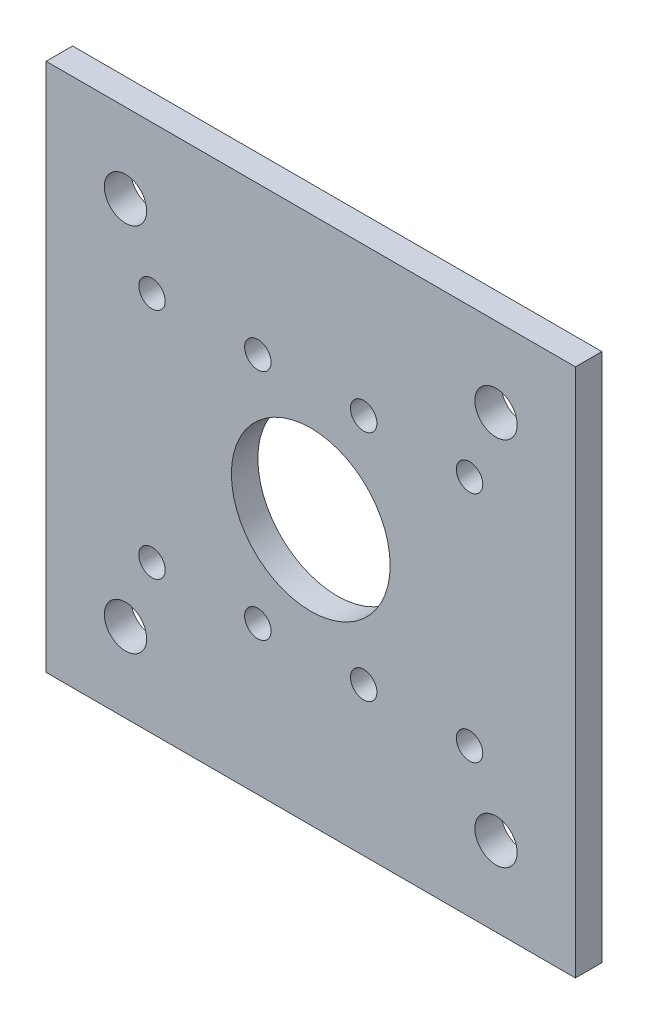
SolidWorks part; units mm, degrees
material "6063-T1"
ref_plane "Front Plane" through (0, 0, 0) normal (0, 0, 1) x (1, 0, 0)
ref_plane "Top Plane" through (0, 0, 0) normal (0, 1, 0) x (1, 0, 0)
ref_plane "Right Plane" through (0, 0, 0) normal (1, 0, 0) x (0, 0, -1)
sketch "Sketch1" plane through (0, 0, 0) normal (0, 0, 1) x (1, 0, 0)
  line L1 (0, 0) -> (100, 0)
  line L2 (0, 0) -> (0, 100)
  line L3 (0, 100) -> (100, 100)
  line L4 (100, 0) -> (100, 100)
  circle A1 centre (15, 85) radius 4
  circle A2 centre (85, 85) radius 4
  circle A3 centre (85, 15) radius 4
  circle A4 centre (15, 15) radius 4
  circle A5 centre (50, 50) radius 15
  dimension "D3" = 30
  dimension "D4" = 50
  dimension "D5" = 50
  dimension "D6" = 8
  dimension "D7" = 8
  dimension "D8" = 8
  dimension "D9" = 8
  dimension "D10" = 15
  dimension "D11" = 15
  dimension "D12" = 15
  dimension "D13" = 15
  dimension "D14" = 15
  dimension "D15" = 15
  dimension "D16" = 15
  dimension "D17" = 15
  dimension "D1" = 100
  dimension "D2" = 100
extrude "Boss-Extrude1" add sketch "Sketch1" along normal blind 5
sketch "Sketch2" plane through (0, 0, 5) normal (0, 0, 1) x (1, 0, 0)
  line L0 (0, 100) -> (0, 0) construction
  line L1 (100, 0) -> (100, 100) construction
  line L2 (100, 100) -> (0, 100) construction
  line L3 (0, 0) -> (100, 0) construction
  circle A1 centre (20, 72) radius 2.5
  circle A2 centre (40, 72) radius 2.5
  circle A3 centre (60, 72) radius 2.5
  circle A4 centre (80, 72) radius 2.5
  circle A5 centre (80, 28) radius 2.5
  circle A6 centre (60, 28) radius 2.5
  circle A7 centre (40, 28) radius 2.5
  circle A8 centre (20, 28) radius 2.5
  dimension "D1" = 5
  dimension "D2" = 20
  dimension "D3" = 20
  dimension "D4" = 20
  dimension "D5" = 20
  dimension "D6" = 20
  dimension "D7" = 20
  dimension "D8" = 20
  dimension "D9" = 20
  dimension "D10" = 28
  dimension "D11" = 28
  dimension "D12" = 28
  dimension "D13" = 28
  dimension "D14" = 28
  dimension "D15" = 28
  dimension "D16" = 28
  dimension "D17" = 28
extrude "Cut-Extrude1" cut sketch "Sketch2" against normal blind 10
